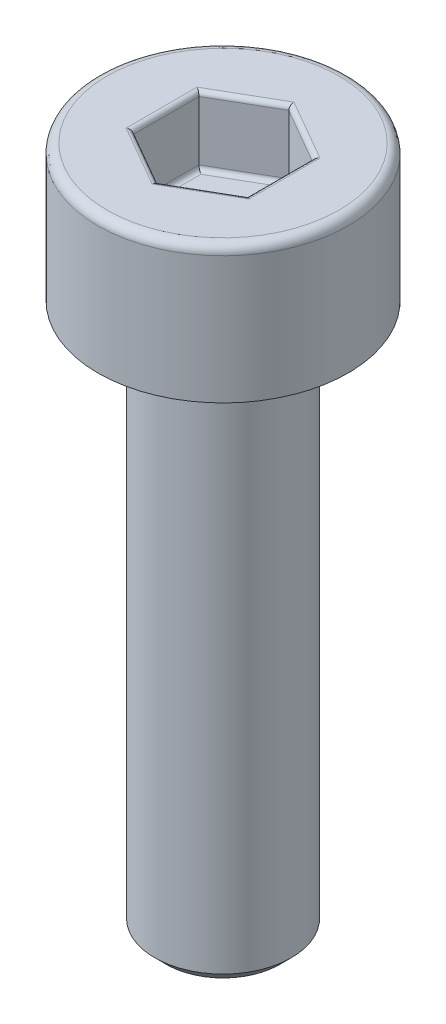
SolidWorks part; units mm, degrees
ref_plane "Front Plane" through (0, 0, 0) normal (0, 0, 1) x (1, 0, 0)
ref_plane "Top Plane" through (0, 0, 0) normal (0, 1, 0) x (1, 0, 0)
ref_plane "Right Plane" through (0, 0, 0) normal (1, 0, 0) x (0, 0, -1)
sketch "Sketch1" plane through (0, 0, 0) normal (0, 0, 1) x (1, 0, 0)
  line L0 (0, 0) -> (0, -47.0967) construction
  line L1 (0, -15) -> (-1.5, -15)
  line L2 (-1.5, -15) -> (-1.5, -3)
  line L3 (-1.5, -3) -> (-2.75, -3)
  line L4 (-2.75, -3) -> (-2.75, 0)
  line L5 (-2.75, 0) -> (0, 0)
  line L6 (0, 0) -> (0, -15)
  dimension "d" = 3
  dimension "l" = 15
  dimension "k" = 3
  dimension "dk" = 5.5
revolve "Revolve1" add sketch "Sketch1" angle 360 about L0
chamfer "Chamfer1" distance 0.25 angle 45 2 edges at (0, -3, 1.5) (0, -15, 1.5)
fillet "Fillet1" radius 0.2 1 edges at (0, 0, 2.75)
sketch "Sketch2" plane through (0, 0, 0) normal (0, 1, 0) x (1, 0, 0)
  line L1 (0, 1.4434) -> (-1.25, 0.7217)
  line L2 (-1.25, 0.7217) -> (-1.25, -0.7217)
  line L3 (-1.25, -0.7217) -> (0, -1.4434)
  line L4 (0, -1.4434) -> (1.25, -0.7217)
  line L5 (1.25, -0.7217) -> (1.25, 0.7217)
  line L6 (1.25, 0.7217) -> (0, 1.4434)
  circle A0 centre (0, 0) radius 1.25 construction
  dimension "s" = 2.5
extrude "Cut-Extrude1" cut sketch "Sketch2" against normal blind 1.5
fillet "Fillet2" radius 0.1 12 edges at (-0.625, 0, -1.0825) (-1.25, 0, 0) (-0.625, 0, 1.0825) (0.625, 0, 1.0825) (1.25, 0, 0) (0.625, 0, -1.0825) (1.25, -1.5, 0) (0.625, -1.5, 1.0825) (-0.625, -1.5, 1.0825) (-1.25, -1.5, 0) (-0.625, -1.5, -1.0825) (0.625, -1.5, -1.0825)
